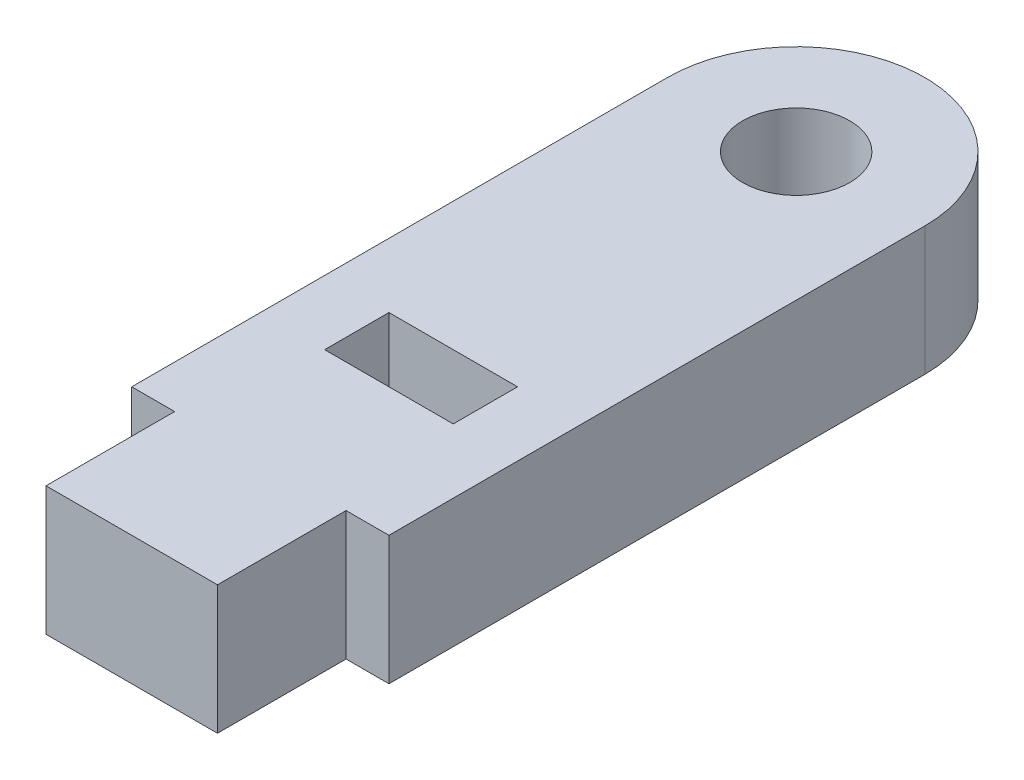
SolidWorks part; units mm, degrees
ref_plane "Front Plane" through (0, 0, 0) normal (0, 0, 1) x (1, 0, 0)
ref_plane "Top Plane" through (0, 0, 0) normal (0, 1, 0) x (1, 0, 0)
ref_plane "Right Plane" through (0, 0, 0) normal (1, 0, 0) x (0, 0, -1)
other "Configuration Table"
sketch "Sketch1" plane through (0, 0, 0) normal (0, 1, 0) x (1, 0, 0)
  line L0 (0, -25) -> (0, -17.5) construction
  line L2 (-6, 0) -> (-6, -25)
  line L4 (6, 0) -> (6, -25)
  line L5 (4, -25) -> (6, -25)
  line L6 (-3, -16) -> (3, -16)
  line L7 (-3, -16) -> (-3, -19)
  line L8 (-3, -19) -> (3, -19)
  line L9 (3, -16) -> (3, -19)
  line L10 (-3, -16) -> (3, -19) construction
  line L11 (-3, -19) -> (3, -16) construction
  line L13 (-4, -25) -> (-4, -31)
  line L14 (-4, -31) -> (4, -31)
  line L15 (4, -25) -> (4, -31)
  line L16 (-6, -25) -> (-4, -25)
  circle A0 centre (0, 0) radius 2.5
  arc A1 (-6, 0) -> (6, 0) centre (0, 0) cw
  dimension "D4" = 5
  dimension "D1" = 25
  dimension "D2" = 12
  dimension "D3" = 7.5
  dimension "D5" = 3
  dimension "D6" = 6
  dimension "D7" = 6
  dimension "D8" = 8
extrude "Boss-Extrude1" add sketch "Sketch1" along normal blind 6
